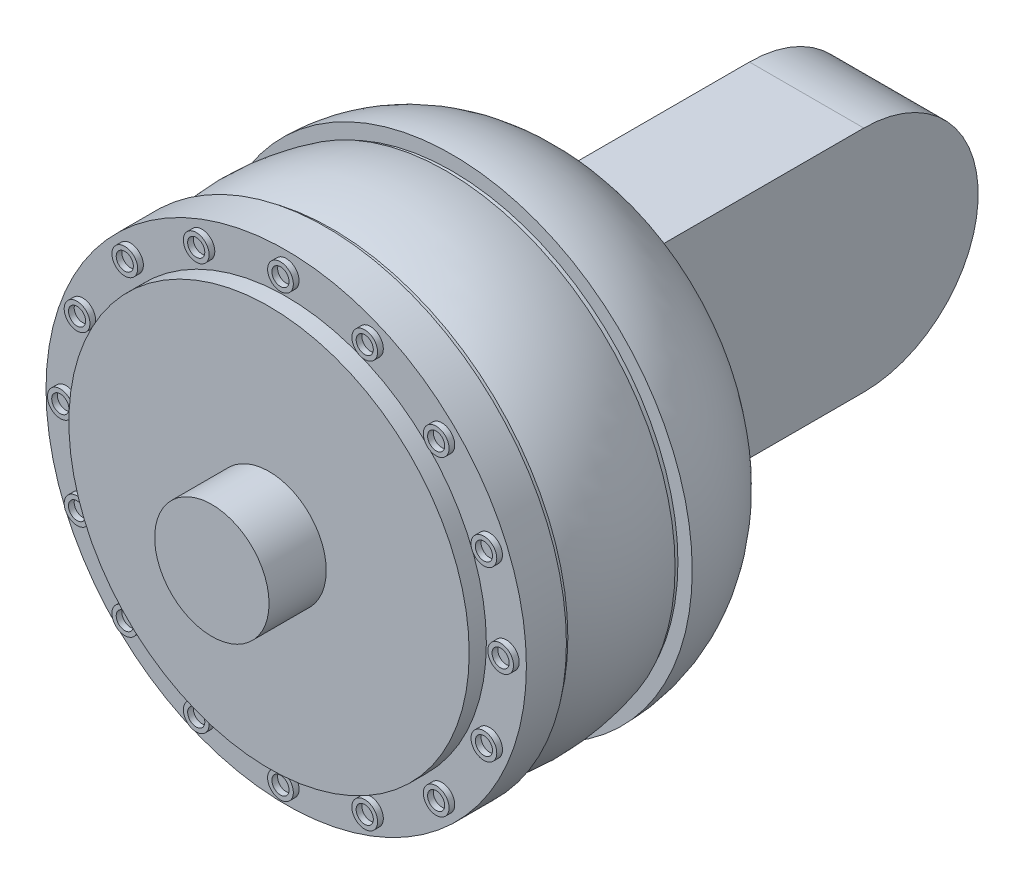
SolidWorks part; units mm, degrees
ref_plane "Front Plane" through (0, 0, 0) normal (0, 0, 1) x (1, 0, 0)
ref_plane "Top Plane" through (0, 0, 0) normal (0, 1, 0) x (1, 0, 0)
ref_plane "Right Plane" through (0, 0, 0) normal (1, 0, 0) x (0, 0, -1)
sketch "Sketch1" plane through (0, 0, 0) normal (0, 1, 0) x (1, 0, 0)
  line L0 (0, 0) -> (0, -20)
  line L1 (0, -20) -> (-42, -20)
  line L2 (-32, 0) -> (0, 0)
  arc A0 (-42, -20) -> (-32, 0) centre (-17, -20) cw
  dimension "D3" = 25
  dimension "D1" = 20
  dimension "D2" = 42
revolve "Revolve1" add sketch "Sketch1" angle 360 about L0
sketch "Sketch2" plane through (0, 0, 20) normal (0, 0, 1) x (1, 0, 0)
  circle A0 centre (0, 0) radius 39.5
  dimension "D1" = 79
extrude "Boss-Extrude1" add sketch "Sketch2" along normal blind 1
sketch "Sketch3" plane through (0, 0, 0) normal (0, 1, 0) x (1, 0, 0)
  line L0 (0, -21) -> (-40, -21)
  line L1 (-39.5, -21) -> (39.5, -21) construction
  line L2 (0, -21) -> (0, -41)
  line L3 (0, -41) -> (-40.0035, -41)
  arc A1 (-40, -21) -> (-40.0035, -41) centre (-4.3787, -31.0062) ccw
  dimension "D3" = 37
  dimension "D1" = 40
  dimension "D2" = 20
revolve "Revolve2" add sketch "Sketch3" angle 360 about L2
sketch "Sketch4" plane through (0, 0, 41) normal (0, 0, 1) x (1, 0, 0)
  circle A0 centre (0, 0) radius 41.25
  dimension "D1" = 82.5
extrude "Boss-Extrude2" add sketch "Sketch4" along normal blind 1
sketch "Sketch5" plane through (0, 0, 42) normal (0, 0, 1) x (1, 0, 0)
  circle A0 centre (0, 0) radius 42
  dimension "D1" = 84
extrude "Boss-Extrude3" add sketch "Sketch5" along normal blind 7
sketch "Sketch6" plane through (0, 0, 49) normal (0, 0, 1) x (1, 0, 0)
  circle A0 centre (0, 0) radius 35
  dimension "D1" = 70
extrude "Boss-Extrude4" add sketch "Sketch6" along normal blind 3
sketch "Sketch7" plane through (0, 0, 49) normal (0, 0, 1) x (1, 0, 0)
  circle A3 centre (38.5, 0) radius 2.25
  circle A4 centre (38.5, 0) radius 1.5
  dimension "D1" = 4.5
  dimension "D2" = 3
extrude "Boss-Extrude5" add sketch "Sketch7" along normal blind 1
pattern_circular "CirPattern1" count 16 over 360 about axis through (0, 0, 0) along (0, 0, 1) of "Boss-Extrude5"
sketch "Sketch8" plane through (0, 0, 0) normal (0, 0, -1) x (-1, 0, 0)
  line L1 (-10, 20) -> (10, 20)
  line L2 (-10, 20) -> (-10, -20)
  line L3 (-10, -20) -> (10, -20)
  line L4 (10, 20) -> (10, -20)
  line L5 (-10, 20) -> (10, -20) construction
  line L6 (-10, -20) -> (10, 20) construction
  point P0 (0, 0)
  dimension "D1" = 40
  dimension "D2" = 20
extrude "Boss-Extrude6" add sketch "Sketch8" along normal blind 42
sketch "Sketch10" plane through (-10, 0, 0) normal (-1, 0, 0) x (0, 0, 1)
  line L0 (-42, -20) -> (-42, 20) construction
  circle A0 centre (-42, 0) radius 20
extrude "Boss-Extrude7" add sketch "Sketch10" against normal up to surface (20 mm away) up to face at (10, 0, -21)
sketch "Sketch11" plane through (-10, 0, 0) normal (-1, 0, 0) x (0, 0, 1)
  circle A0 centre (-42, 0) radius 10
  dimension "D1" = 20
extrude "Boss-Extrude8" add sketch "Sketch11" along normal blind 10
sketch "Sketch12" plane through (0, 0, 52) normal (0, 0, 1) x (1, 0, 0)
  circle A0 centre (0, 0) radius 10
  dimension "D1" = 20
extrude "Boss-Extrude9" add sketch "Sketch12" along normal blind 10
